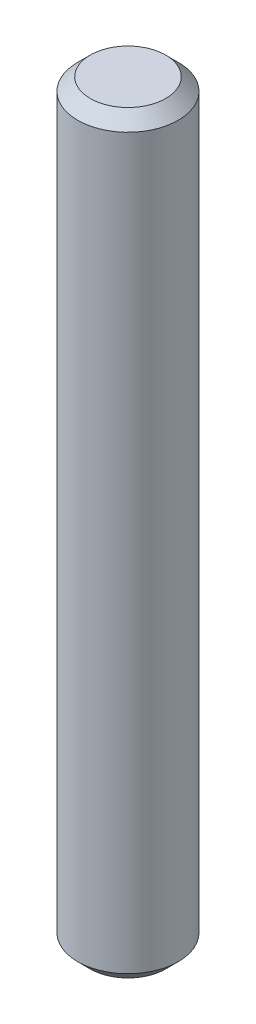
SolidWorks part; units mm, degrees
ref_plane "Front Plane" through (0, 0, 0) normal (0, 0, 1) x (1, 0, 0)
ref_plane "Top Plane" through (0, 0, 0) normal (0, 1, 0) x (1, 0, 0)
ref_plane "Right Plane" through (0, 0, 0) normal (1, 0, 0) x (0, 0, -1)
sketch "Sketch1" plane through (0, 0, 0) normal (0, 1, 0) x (1, 0, 0)
  circle A0 centre (0, 0) radius 2
extrude "Boss-Extrude1" add sketch "Sketch1" along normal blind 30
chamfer "Chamfer3" distance 0.5 angle 45 1 edges at (0, 0, 2)
chamfer "Chamfer4" distance 0.5 angle 45 1 edges at (0, 30, 2)
